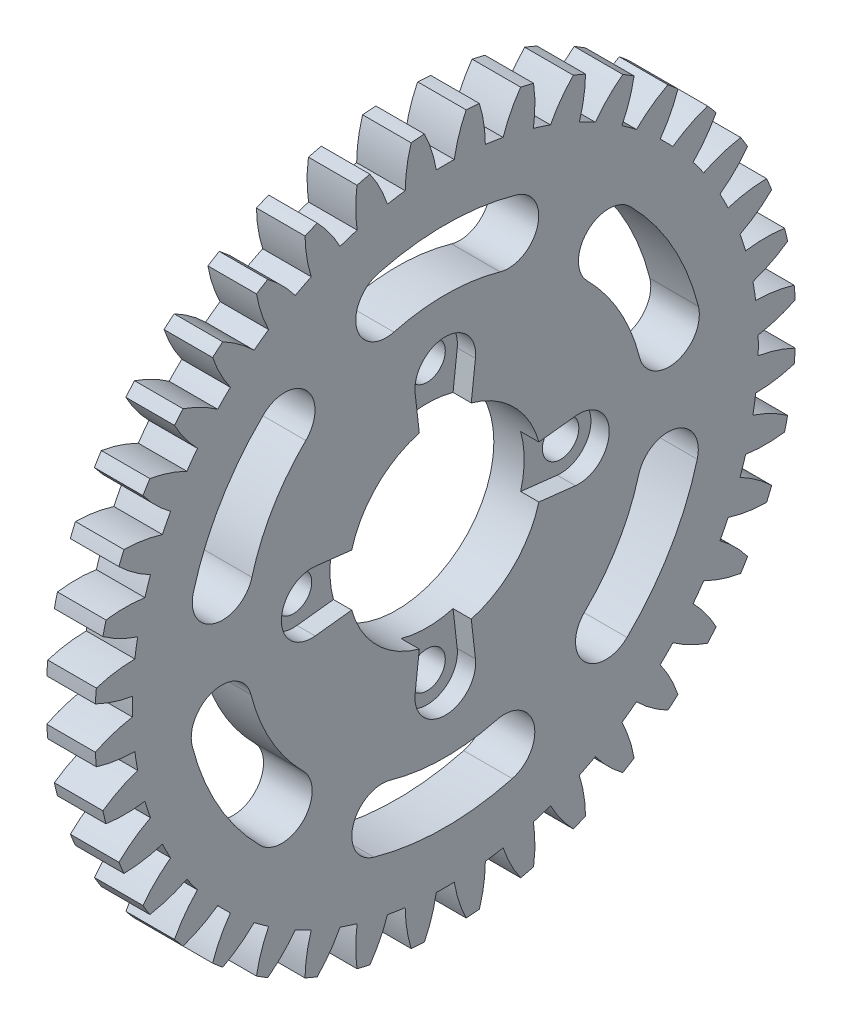
SolidWorks part; units mm, degrees
material "POM 乙缩醛共聚物"
ref_plane "Plane1" through (0, 0, 0) normal (0, 0, 1) x (1, 0, 0)
ref_plane "Plane2" through (0, 0, 0) normal (0, 1, 0) x (1, 0, 0)
ref_plane "Plane3" through (0, 0, 0) normal (1, 0, 0) x (0, 0, -1)
sketch "HoldingSke" plane through (0, 0, 0) normal (0, 1, 0) x (1, 0, 0)
  line L0 (0, 0) -> (0.5571, -0.4675)
  line L1 (-15, 0) -> (100, 0) construction
  line L2 (0, 0) -> (-2.1039, 2.3779)
  line L3 (0, 0) -> (-11.863, 4.5341)
  line L4 (0, 0) -> (6.6156, 5.5511)
  line L5 (0, 0) -> (-46.8476, -17.4728)
  line L6 (0, 0) -> (-3.3159, -2.2372)
  line L7 (-2.1039, 2.3779) -> (8.6586, 51.2059)
  line L8 (-76.2, 54.61) -> (-73.9, 54.61)
  line L9 (-67.7845, 28.3722) -> (-49.3413, 33.142)
  line L10 (-76.2, 71.12) -> (104.1128, 71.12)
  line L11 (0, 0) -> (-4, 0)
  line L12 (-76.2, 101.6) -> (-76.151, 101.6)
  line L13 (24.9733, 27.94) -> (52.9518, 28.4284)
  line L14 (24.9733, 27.94) -> (24.9743, 27.94)
  line L15 (24.9733, 27.94) -> (100.4006, 29.5858)
  line L16 (-63.627, -1.375) -> (-12.827, -1.375)
  circle A0 centre (0, 0) radius 8
  circle A1 centre (0, 0) radius 25.7803
  circle A2 centre (0, 0) radius 37.5
  circle A3 centre (0, 0) radius 8
  dimension "MHD" = 51.5605
  dimension "Hub_dia" = 75
  dimension "Bore" = 16
  dimension "MBD" = 16
  dimension "Num_teeth" = 40
  dimension "Pitch" = 0.7273
  dimension "Overall_len" = 50
  dimension "Show_teeth" = 40
  dimension "Thickness" = 4
  dimension "OAL" = 50.0001
  dimension "T_dim" = 2.3
  dimension "Ap" = 14.5
  dimension "H" = 19.05
  dimension "Pitch_radius" = 180.3128
  dimension "Width" = 4
  dimension "Backlash" = 0.049
  dimension "Addendum_fac" = 1
  dimension "Dedendum_fac" = 1.25
  dimension "Clearance_fac" = 0.25
  dimension "Dedendum_add" = 0.001
  dimension "Module" = 1.375
sketch "BasProSke" plane through (0, 0, 0) normal (0, 1, 0) x (1, 0, 0)
  line L0 (-10, 0) -> (60, 0) construction
  line L1 (0, 0) -> (0, 28.875)
  line L2 (0, 0) -> (4, 0)
  line L3 (4, 0) -> (4, 28.875)
  line L4 (4, 28.875) -> (0, 28.875)
  dimension "Thickness" = 4
  dimension "Diameter" = 57.75
revolve "Base-Revolve" add sketch "BasProSke" angle 360 about L0
sketch "TooCutSke" plane through (0, 0, 0) normal (1, 0, 0) x (0, 0, -1)
  line L1 (0, 0) -> (0, 107) construction
  line L2 (0, 0) -> (-1.1654, 27.4753) construction
  line L3 (0, 0) -> (-4.3124, 54.7946) construction
  line L4 (-1.1654, 27.4753) -> (-2.1562, 27.3973) construction
  arc A0 (0.7399, 25.7696) -> (-0.7399, 25.7696) centre (0, 0) ccw
  arc A1 (1.7331, 28.8484) -> (-1.7331, 28.8484) centre (0, 0) ccw
  circle A2 centre (0, 0) radius 27.5 construction
  circle A3 centre (0, 0) radius 26.6241 construction
  arc A4 (-0.7399, 25.7696) -> (-1.7331, 28.8484) centre (-11.5914, 23.9683) ccw
  arc A5 (1.7331, 28.8484) -> (0.7399, 25.7696) centre (11.5914, 23.9683) ccw
  dimension "Root_dia" = 51.5605
  dimension "Overcut_dia" = 57.8008
  dimension "Pitch_dia" = 55
  dimension "Base_dia" = 53.2481
  dimension "Flank_rad" = 11
  dimension "Half_ang" = 4.5
  dimension "Half_CT" = 0.9939
extrude "ToothCut" cut sketch "TooCutSke" along normal through all
fillet "Breaks" [suppressed] radius 0.0275
fillet "RootFillets" [suppressed] radius 0.3448
pattern_circular "TeethCuts" count 40 every 9 about axis through (-10, 0, 0) along (1, 0, 0) of "ToothCut", "RootFillets", "Breaks"
sketch "HubNeaOneSke" plane through (0, 0, 0) normal (-1, 0, 0) x (0, 0, 1)
  circle A0 centre (0, 0) radius 25.7803
  dimension "Diameter" = 51.5605
extrude "HubNearOne" [suppressed] add sketch "HubNeaOneSke" along normal blind 46.0001
sketch "HubNeaBotSke" plane through (0, 0, 0) normal (-1, 0, 0) x (0, 0, 1)
  circle A0 centre (0, 0) radius 25.7803
  dimension "Diameter" = 51.5605
extrude "HubNearBoth" [suppressed] add sketch "HubNeaBotSke" along normal blind 23
ref_plane "FarPln" through (4, 0, 0) normal (1, 0, 0) x (0, 0, -1)
sketch "HubFarSke" plane through (4, 0, 0) normal (1, 0, 0) x (0, 0, -1)
  circle A0 centre (0, 0) radius 25.7803
  dimension "Diameter" = 51.5605
extrude "HubFar" [suppressed] add sketch "HubFarSke" along normal blind 23
sketch "BorSke" plane through (0, 0, 0) normal (1, 0, 0) x (0, 0, -1)
  circle A0 centre (0, 0) radius 8
  dimension "Diameter" = 16
extrude "Bore" cut sketch "BorSke" along normal mid plane 100.0001
sketch "KeySke" plane through (0, 0, 0) normal (1, 0, 0) x (0, 0, -1)
  line L0 (-2.5, 0) -> (-2.5, 10.3)
  line L1 (-2.5, 10.3) -> (2.5, 10.3)
  line L2 (2.5, 10.3) -> (2.5, 0)
  line L3 (0, 0) -> (0, 34) construction
  line L4 (-2.5, 0) -> (2.5, 0)
  dimension "Offset" = 10.3
  dimension "Width" = 5
extrude "Keyway" [suppressed] cut sketch "KeySke" along normal mid plane 100.0001
pattern_circular "Keyway2" [suppressed] count 2 every 90 about axis through (-10, 0, 0) along (1, 0, 0)
sketch "草图1" plane through (4, 0, 0) normal (1, 0, 0) x (0, 0, -1)
  line L0 (10.7159, 2.4838) -> (7.7085, 2.1398)
  line L1 (10.7159, -2.4838) -> (7.7085, -2.1398)
  line L2 (-2.4838, -10.7159) -> (-2.1398, -7.7085)
  line L3 (2.4838, -10.7159) -> (2.1398, -7.7085)
  line L4 (-10.7159, 2.4838) -> (-7.7085, 2.1398)
  line L5 (-10.7159, -2.4838) -> (-7.7085, -2.1398)
  line L6 (2.4838, 10.7159) -> (2.1398, 7.7085)
  line L7 (-2.4838, 10.7159) -> (-2.1398, 7.7085)
  arc A0 (10.7159, -2.4838) -> (10.7159, 2.4838) centre (0, 0) ccw
  circle A1 centre (11, 0) radius 1.5
  arc A2 (10.7159, -2.4838) -> (10.7159, 2.4838) centre (11, 0) ccw
  circle A3 centre (0, 0) radius 8 construction
  arc A4 (-2.4838, -10.7159) -> (2.4838, -10.7159) centre (0, -11) ccw
  circle A5 centre (0, -11) radius 1.5
  arc A6 (-10.7159, 2.4838) -> (-10.7159, -2.4838) centre (-11, 0) ccw
  circle A7 centre (-11, 0) radius 1.5
  arc A8 (2.4838, 10.7159) -> (-2.4838, 10.7159) centre (0, 11) ccw
  circle A9 centre (0, 11) radius 1.5
  circle A10 centre (0, 0) radius 8
  point P31 (0, 0)
  dimension "D1" = 3
  dimension "D2" = 22
  dimension "D3" = 5
  dimension "D5" = 11
  dimension "D6" = 11
  dimension "D4" = 4
extrude "切除-拉伸2" cut sketch "草图1" against normal blind 1.5 contours A0 A2 A1 | A0 A1 | A0 A1 | A10 L1 A0 A1 L0 | A10 L2 A4 L3 A5 | A5 | A10 L4 A6 L5 A7 | A7 | A9 | A10 L6 A8 L7 A9
sketch "草图3" plane through (4, 0, 0) normal (1, 0, 0) x (0, 0, -1)
  line L0 (10.7159, 2.4838) -> (7.7085, 2.1398) construction
  line L1 (10.7159, -2.4838) -> (7.7085, -2.1398) construction
  line L2 (2.4838, -10.7159) -> (2.1398, -7.7085) construction
  line L3 (-2.4838, -10.7159) -> (-2.1398, -7.7085) construction
  line L4 (-10.7159, -2.4838) -> (-7.7085, -2.1398) construction
  line L5 (-10.7159, 2.4838) -> (-7.7085, 2.1398) construction
  line L6 (-2.4838, 10.7159) -> (-2.1398, 7.7085) construction
  line L7 (2.4838, 10.7159) -> (2.1398, 7.7085) construction
  line L8 (10.7159, 2.4838) -> (7.7085, 2.1398)
  line L9 (10.7159, -2.4838) -> (7.7085, -2.1398)
  line L10 (2.4838, -10.7159) -> (2.1398, -7.7085)
  line L11 (-2.4838, -10.7159) -> (-2.1398, -7.7085)
  line L12 (-10.7159, -2.4838) -> (-7.7085, -2.1398)
  line L13 (-10.7159, 2.4838) -> (-7.7085, 2.1398)
  line L14 (-2.4838, 10.7159) -> (-2.1398, 7.7085)
  line L15 (2.4838, 10.7159) -> (2.1398, 7.7085)
  line L16 (0, 0) -> (6.2134, 0) construction
  arc A0 (10.7159, -2.4838) -> (10.7159, 2.4838) centre (11, 0) ccw construction
  arc A1 (2.1398, -7.7085) -> (7.7085, -2.1398) centre (0, 0) ccw construction
  arc A2 (-2.4838, -10.7159) -> (2.4838, -10.7159) centre (0, -11) ccw construction
  arc A3 (-7.7085, -2.1398) -> (-2.1398, -7.7085) centre (0, 0) ccw construction
  arc A4 (-10.7159, 2.4838) -> (-10.7159, -2.4838) centre (-11, 0) ccw construction
  arc A5 (-2.1398, 7.7085) -> (-7.7085, 2.1398) centre (0, 0) ccw construction
  arc A6 (2.4838, 10.7159) -> (-2.4838, 10.7159) centre (0, 11) ccw construction
  arc A7 (7.7085, 2.1398) -> (2.1398, 7.7085) centre (0, 0) ccw construction
  arc A8 (10.7159, -2.4838) -> (10.7159, 2.4838) centre (11, 0) ccw
  arc A9 (2.1398, -7.7085) -> (7.7085, -2.1398) centre (0, 0) ccw
  arc A10 (-2.4838, -10.7159) -> (2.4838, -10.7159) centre (0, -11) ccw
  arc A11 (-7.7085, -2.1398) -> (-2.1398, -7.7085) centre (0, 0) ccw
  arc A12 (-10.7159, 2.4838) -> (-10.7159, -2.4838) centre (-11, 0) ccw
  arc A13 (-2.1398, 7.7085) -> (-7.7085, 2.1398) centre (0, 0) ccw
  arc A14 (2.4838, 10.7159) -> (-2.4838, 10.7159) centre (0, 11) ccw
  arc A15 (7.7085, 2.1398) -> (2.1398, 7.7085) centre (0, 0) ccw
  circle A16 centre (0, 11) radius 1.5
  circle A17 centre (0, -11) radius 1.5
  circle A18 centre (11, 0) radius 1.5
  circle A19 centre (-11, 0) radius 1.5
  arc A21 (13.4665, 13.4034) -> (18.4254, 4.6371) centre (0, 0) cw construction
  arc A22 (20.8499, 5.2473) -> (15.2385, 15.1671) centre (0, 0) ccw
  arc A23 (16.001, 4.027) -> (11.6946, 11.6398) centre (0, 0) ccw
  arc A24 (16.001, 4.027) -> (20.8499, 5.2473) centre (18.4254, 4.6371) ccw
  arc A25 (15.2385, 15.1671) -> (11.6946, 11.6398) centre (13.4665, 13.4034) ccw
  arc A26 (11.488, -11.8438) -> (15.9277, -4.3079) centre (0, 0) ccw
  arc A27 (11.488, -11.8438) -> (14.9692, -15.4329) centre (13.2286, -13.6384) ccw
  arc A28 (20.7543, -5.6134) -> (15.9277, -4.3079) centre (18.341, -4.9606) ccw
  arc A29 (14.9692, -15.4329) -> (20.7543, -5.6134) centre (0, 0) ccw
  arc A30 (18.341, -4.9606) -> (13.2286, -13.6384) centre (0, 0) cw construction
  arc A31 (-4.5131, -15.8708) -> (4.2331, -15.9478) centre (0, 0) ccw
  arc A32 (-4.5131, -15.8708) -> (-5.8807, -20.6801) centre (-5.1969, -18.2755) ccw
  arc A33 (5.5158, -20.7804) -> (4.2331, -15.9478) centre (4.8745, -18.3641) ccw
  arc A34 (-5.8807, -20.6801) -> (5.5158, -20.7804) centre (0, 0) ccw
  arc A35 (4.8745, -18.3641) -> (-5.1969, -18.2755) centre (0, 0) cw construction
  arc A36 (-16.001, -4.027) -> (-11.6946, -11.6398) centre (0, 0) ccw
  arc A37 (-16.001, -4.027) -> (-20.8499, -5.2473) centre (-18.4254, -4.6371) ccw
  arc A38 (-15.2385, -15.1671) -> (-11.6946, -11.6398) centre (-13.4665, -13.4034) ccw
  arc A39 (-20.8499, -5.2473) -> (-15.2385, -15.1671) centre (0, 0) ccw
  arc A40 (-13.4665, -13.4034) -> (-18.4254, -4.6371) centre (0, 0) cw construction
  arc A41 (-11.488, 11.8438) -> (-15.9277, 4.3079) centre (0, 0) ccw
  arc A42 (-11.488, 11.8438) -> (-14.9692, 15.4329) centre (-13.2286, 13.6384) ccw
  arc A43 (-20.7543, 5.6134) -> (-15.9277, 4.3079) centre (-18.341, 4.9606) ccw
  arc A44 (-14.9692, 15.4329) -> (-20.7543, 5.6134) centre (0, 0) ccw
  arc A45 (-18.341, 4.9606) -> (-13.2286, 13.6384) centre (0, 0) cw construction
  arc A46 (4.5131, 15.8708) -> (-4.2331, 15.9478) centre (0, 0) ccw
  arc A47 (4.5131, 15.8708) -> (5.8807, 20.6801) centre (5.1969, 18.2755) ccw
  arc A48 (-5.5158, 20.7804) -> (-4.2331, 15.9478) centre (-4.8745, 18.3641) ccw
  arc A49 (5.8807, 20.6801) -> (-5.5158, 20.7804) centre (0, 0) ccw
  arc A50 (-4.8745, 18.3641) -> (5.1969, 18.2755) centre (0, 0) cw construction
  arc A160 (-28.8237, 1.7209) -> (-25.7696, 0.7399) centre (-23.9683, 11.5914) ccw
  arc A161 (-25.7696, 0.7399) -> (-25.7696, -0.7399) centre (0, 0) ccw
  arc A162 (-25.7696, -0.7399) -> (-28.8237, -1.7209) centre (-23.9683, -11.5914) ccw
  arc A163 (-28.8237, -1.7209) -> (-28.738, -2.8093) centre (0, 0) ccw
  arc A164 (-28.738, -2.8093) -> (-25.5681, -3.3005) centre (-25.4865, 7.6992) ccw
  arc A165 (-25.5681, -3.3005) -> (-25.3366, -4.762) centre (0, 0) ccw
  arc A166 (-25.3366, -4.762) -> (-28.1996, -6.2088) centre (-21.8599, -15.1981) ccw
  arc A167 (-28.1996, -6.2088) -> (-27.9447, -7.2703) centre (0, 0) ccw
  arc A168 (-27.9447, -7.2703) -> (-24.737, -7.2596) centre (-26.3772, 3.6174) ccw
  arc A169 (-24.737, -7.2596) -> (-24.2797, -8.6669) centre (0, 0) ccw
  arc A170 (-24.2797, -8.6669) -> (-26.8811, -10.5437) centre (-19.2133, -18.4307) ccw
  arc A171 (-26.8811, -10.5437) -> (-26.4634, -11.5523) centre (0, 0) ccw
  arc A172 (-26.4634, -11.5523) -> (-23.2968, -11.0399) centre (-26.6183, -0.5534) ccw
  arc A173 (-23.2968, -11.0399) -> (-22.625, -12.3584) centre (0, 0) ccw
  arc A174 (-22.625, -12.3584) -> (-24.9008, -14.619) centre (-16.0936, -21.2094) ccw
  arc A175 (-24.9008, -14.619) -> (-24.3304, -15.5499) centre (0, 0) ccw
  arc A176 (-24.3304, -15.5499) -> (-21.2829, -14.5485) centre (-26.204, -4.7106) ccw
  arc A177 (-21.2829, -14.5485) -> (-20.4132, -15.7456) centre (0, 0) ccw
  arc A178 (-20.4132, -15.7456) -> (-22.3073, -18.3344) centre (-12.5775, -23.4658) ccw
  arc A179 (-22.3073, -18.3344) -> (-21.5983, -19.1645) centre (0, 0) ccw
  arc A180 (-21.5983, -19.1645) -> (-18.745, -17.6987) centre (-25.1445, -8.7518) ccw
  arc A181 (-18.745, -17.6987) -> (-17.6987, -18.745) centre (0, 0) ccw
  arc A182 (-17.6987, -18.745) -> (-19.1645, -21.5983) centre (-8.7518, -25.1445) ccw
  arc A183 (-19.1645, -21.5983) -> (-18.3344, -22.3073) centre (0, 0) ccw
  arc A184 (-18.3344, -22.3073) -> (-15.7456, -20.4132) centre (-23.4658, -12.5775) ccw
  arc A185 (-15.7456, -20.4132) -> (-14.5485, -21.2829) centre (0, 0) ccw
  arc A186 (-14.5485, -21.2829) -> (-15.5499, -24.3304) centre (-4.7106, -26.204) ccw
  arc A187 (-15.5499, -24.3304) -> (-14.619, -24.9008) centre (0, 0) ccw
  arc A188 (-14.619, -24.9008) -> (-12.3584, -22.625) centre (-21.2094, -16.0936) ccw
  arc A189 (-12.3584, -22.625) -> (-11.0399, -23.2968) centre (0, 0) ccw
  arc A190 (-11.0399, -23.2968) -> (-11.5523, -26.4634) centre (-0.5534, -26.6183) ccw
  arc A191 (-11.5523, -26.4634) -> (-10.5437, -26.8811) centre (0, 0) ccw
  arc A192 (-10.5437, -26.8811) -> (-8.6669, -24.2797) centre (-18.4307, -19.2133) ccw
  arc A193 (-8.6669, -24.2797) -> (-7.2596, -24.737) centre (0, 0) ccw
  arc A194 (-7.2596, -24.737) -> (-7.2703, -27.9447) centre (3.6174, -26.3772) ccw
  arc A195 (-7.2703, -27.9447) -> (-6.2088, -28.1996) centre (0, 0) ccw
  arc A196 (-6.2088, -28.1996) -> (-4.762, -25.3366) centre (-15.1981, -21.8599) ccw
  arc A197 (-4.762, -25.3366) -> (-3.3005, -25.5681) centre (0, 0) ccw
  arc A198 (-3.3005, -25.5681) -> (-2.8093, -28.738) centre (7.6992, -25.4865) ccw
  arc A199 (-2.8093, -28.738) -> (-1.7209, -28.8237) centre (0, 0) ccw
  arc A200 (-1.7209, -28.8237) -> (-0.7399, -25.7696) centre (-11.5914, -23.9683) ccw
  arc A201 (-0.7399, -25.7696) -> (0.7399, -25.7696) centre (0, 0) ccw
  arc A202 (0.7399, -25.7696) -> (1.7209, -28.8237) centre (11.5914, -23.9683) ccw
  arc A203 (1.7209, -28.8237) -> (2.8093, -28.738) centre (0, 0) ccw
  arc A204 (2.8093, -28.738) -> (3.3005, -25.5681) centre (-7.6992, -25.4865) ccw
  arc A205 (3.3005, -25.5681) -> (4.762, -25.3366) centre (0, 0) ccw
  arc A206 (4.762, -25.3366) -> (6.2088, -28.1996) centre (15.1981, -21.8599) ccw
  arc A207 (6.2088, -28.1996) -> (7.2703, -27.9447) centre (0, 0) ccw
  arc A208 (7.2703, -27.9447) -> (7.2596, -24.737) centre (-3.6174, -26.3772) ccw
  arc A209 (7.2596, -24.737) -> (8.6669, -24.2797) centre (0, 0) ccw
  arc A210 (8.6669, -24.2797) -> (10.5437, -26.8811) centre (18.4307, -19.2133) ccw
  arc A211 (10.5437, -26.8811) -> (11.5523, -26.4634) centre (0, 0) ccw
  arc A212 (11.5523, -26.4634) -> (11.0399, -23.2968) centre (0.5534, -26.6183) ccw
  arc A213 (11.0399, -23.2968) -> (12.3584, -22.625) centre (0, 0) ccw
  arc A214 (12.3584, -22.625) -> (14.619, -24.9008) centre (21.2094, -16.0936) ccw
  arc A215 (14.619, -24.9008) -> (15.5499, -24.3304) centre (0, 0) ccw
  arc A216 (15.5499, -24.3304) -> (14.5485, -21.2829) centre (4.7106, -26.204) ccw
  arc A217 (14.5485, -21.2829) -> (15.7456, -20.4132) centre (0, 0) ccw
  arc A218 (15.7456, -20.4132) -> (18.3344, -22.3073) centre (23.4658, -12.5775) ccw
  arc A219 (18.3344, -22.3073) -> (19.1645, -21.5983) centre (0, 0) ccw
  arc A220 (19.1645, -21.5983) -> (17.6987, -18.745) centre (8.7518, -25.1445) ccw
  arc A221 (17.6987, -18.745) -> (18.745, -17.6987) centre (0, 0) ccw
  arc A222 (18.745, -17.6987) -> (21.5983, -19.1645) centre (25.1445, -8.7518) ccw
  arc A223 (21.5983, -19.1645) -> (22.3073, -18.3344) centre (0, 0) ccw
  arc A224 (22.3073, -18.3344) -> (20.4132, -15.7456) centre (12.5775, -23.4658) ccw
  arc A225 (20.4132, -15.7456) -> (21.2829, -14.5485) centre (0, 0) ccw
  arc A226 (21.2829, -14.5485) -> (24.3304, -15.5499) centre (26.204, -4.7106) ccw
  arc A227 (24.3304, -15.5499) -> (24.9008, -14.619) centre (0, 0) ccw
  arc A228 (24.9008, -14.619) -> (22.625, -12.3584) centre (16.0936, -21.2094) ccw
  arc A229 (22.625, -12.3584) -> (23.2968, -11.0399) centre (0, 0) ccw
  arc A230 (23.2968, -11.0399) -> (26.4634, -11.5523) centre (26.6183, -0.5534) ccw
  arc A231 (26.4634, -11.5523) -> (26.8811, -10.5437) centre (0, 0) ccw
  arc A232 (26.8811, -10.5437) -> (24.2797, -8.6669) centre (19.2133, -18.4307) ccw
  arc A233 (24.2797, -8.6669) -> (24.737, -7.2596) centre (0, 0) ccw
  arc A234 (24.737, -7.2596) -> (27.9447, -7.2703) centre (26.3772, 3.6174) ccw
  arc A235 (27.9447, -7.2703) -> (28.1996, -6.2088) centre (0, 0) ccw
  arc A236 (28.1996, -6.2088) -> (25.3366, -4.762) centre (21.8599, -15.1981) ccw
  arc A237 (25.3366, -4.762) -> (25.5681, -3.3005) centre (0, 0) ccw
  arc A238 (25.5681, -3.3005) -> (28.738, -2.8093) centre (25.4865, 7.6992) ccw
  arc A239 (28.738, -2.8093) -> (28.8237, -1.7209) centre (0, 0) ccw
  arc A240 (28.8237, -1.7209) -> (25.7696, -0.7399) centre (23.9683, -11.5914) ccw
  arc A241 (25.7696, -0.7399) -> (25.7696, 0.7399) centre (0, 0) ccw
  arc A242 (25.7696, 0.7399) -> (28.8237, 1.7209) centre (23.9683, 11.5914) ccw
  arc A243 (28.8237, 1.7209) -> (28.738, 2.8093) centre (0, 0) ccw
  arc A244 (28.738, 2.8093) -> (25.5681, 3.3005) centre (25.4865, -7.6992) ccw
  arc A245 (25.5681, 3.3005) -> (25.3366, 4.762) centre (0, 0) ccw
  arc A246 (25.3366, 4.762) -> (28.1996, 6.2088) centre (21.8599, 15.1981) ccw
  arc A247 (28.1996, 6.2088) -> (27.9447, 7.2703) centre (0, 0) ccw
  arc A248 (27.9447, 7.2703) -> (24.737, 7.2596) centre (26.3772, -3.6174) ccw
  arc A249 (24.737, 7.2596) -> (24.2797, 8.6669) centre (0, 0) ccw
  arc A250 (24.2797, 8.6669) -> (26.8811, 10.5437) centre (19.2133, 18.4307) ccw
  arc A251 (26.8811, 10.5437) -> (26.4634, 11.5523) centre (0, 0) ccw
  arc A252 (26.4634, 11.5523) -> (23.2968, 11.0399) centre (26.6183, 0.5534) ccw
  arc A253 (23.2968, 11.0399) -> (22.625, 12.3584) centre (0, 0) ccw
  arc A254 (22.625, 12.3584) -> (24.9008, 14.619) centre (16.0936, 21.2094) ccw
  arc A255 (24.9008, 14.619) -> (24.3304, 15.5499) centre (0, 0) ccw
  arc A256 (24.3304, 15.5499) -> (21.2829, 14.5485) centre (26.204, 4.7106) ccw
  arc A257 (21.2829, 14.5485) -> (20.4132, 15.7456) centre (0, 0) ccw
  arc A258 (20.4132, 15.7456) -> (22.3073, 18.3344) centre (12.5775, 23.4658) ccw
  arc A259 (22.3073, 18.3344) -> (21.5983, 19.1645) centre (0, 0) ccw
  arc A260 (21.5983, 19.1645) -> (18.745, 17.6987) centre (25.1445, 8.7518) ccw
  arc A261 (18.745, 17.6987) -> (17.6987, 18.745) centre (0, 0) ccw
  arc A262 (17.6987, 18.745) -> (19.1645, 21.5983) centre (8.7518, 25.1445) ccw
  arc A263 (19.1645, 21.5983) -> (18.3344, 22.3073) centre (0, 0) ccw
  arc A264 (18.3344, 22.3073) -> (15.7456, 20.4132) centre (23.4658, 12.5775) ccw
  arc A265 (15.7456, 20.4132) -> (14.5485, 21.2829) centre (0, 0) ccw
  arc A266 (14.5485, 21.2829) -> (15.5499, 24.3304) centre (4.7106, 26.204) ccw
  arc A267 (15.5499, 24.3304) -> (14.619, 24.9008) centre (0, 0) ccw
  arc A268 (14.619, 24.9008) -> (12.3584, 22.625) centre (21.2094, 16.0936) ccw
  arc A269 (12.3584, 22.625) -> (11.0399, 23.2968) centre (0, 0) ccw
  arc A270 (11.0399, 23.2968) -> (11.5523, 26.4634) centre (0.5534, 26.6183) ccw
  arc A271 (11.5523, 26.4634) -> (10.5437, 26.8811) centre (0, 0) ccw
  arc A272 (10.5437, 26.8811) -> (8.6669, 24.2797) centre (18.4307, 19.2133) ccw
  arc A273 (8.6669, 24.2797) -> (7.2596, 24.737) centre (0, 0) ccw
  arc A274 (7.2596, 24.737) -> (7.2703, 27.9447) centre (-3.6174, 26.3772) ccw
  arc A275 (7.2703, 27.9447) -> (6.2088, 28.1996) centre (0, 0) ccw
  arc A276 (6.2088, 28.1996) -> (4.762, 25.3366) centre (15.1981, 21.8599) ccw
  arc A277 (4.762, 25.3366) -> (3.3005, 25.5681) centre (0, 0) ccw
  arc A278 (3.3005, 25.5681) -> (2.8093, 28.738) centre (-7.6992, 25.4865) ccw
  arc A279 (2.8093, 28.738) -> (1.7209, 28.8237) centre (0, 0) ccw
  arc A280 (1.7209, 28.8237) -> (0.7399, 25.7696) centre (11.5914, 23.9683) ccw
  arc A281 (0.7399, 25.7696) -> (-0.7399, 25.7696) centre (0, 0) ccw
  arc A282 (-0.7399, 25.7696) -> (-1.7209, 28.8237) centre (-11.5914, 23.9683) ccw
  arc A283 (-1.7209, 28.8237) -> (-2.8093, 28.738) centre (0, 0) ccw
  arc A284 (-2.8093, 28.738) -> (-3.3005, 25.5681) centre (7.6992, 25.4865) ccw
  arc A285 (-3.3005, 25.5681) -> (-4.762, 25.3366) centre (0, 0) ccw
  arc A286 (-4.762, 25.3366) -> (-6.2088, 28.1996) centre (-15.1981, 21.8599) ccw
  arc A287 (-6.2088, 28.1996) -> (-7.2703, 27.9447) centre (0, 0) ccw
  arc A288 (-7.2703, 27.9447) -> (-7.2596, 24.737) centre (3.6174, 26.3772) ccw
  arc A289 (-7.2596, 24.737) -> (-8.6669, 24.2797) centre (0, 0) ccw
  arc A290 (-8.6669, 24.2797) -> (-10.5437, 26.8811) centre (-18.4307, 19.2133) ccw
  arc A291 (-10.5437, 26.8811) -> (-11.5523, 26.4634) centre (0, 0) ccw
  arc A292 (-11.5523, 26.4634) -> (-11.0399, 23.2968) centre (-0.5534, 26.6183) ccw
  arc A293 (-11.0399, 23.2968) -> (-12.3584, 22.625) centre (0, 0) ccw
  arc A294 (-12.3584, 22.625) -> (-14.619, 24.9008) centre (-21.2094, 16.0936) ccw
  arc A295 (-14.619, 24.9008) -> (-15.5499, 24.3304) centre (0, 0) ccw
  arc A296 (-15.5499, 24.3304) -> (-14.5485, 21.2829) centre (-4.7106, 26.204) ccw
  arc A297 (-14.5485, 21.2829) -> (-15.7456, 20.4132) centre (0, 0) ccw
  arc A298 (-15.7456, 20.4132) -> (-18.3344, 22.3073) centre (-23.4658, 12.5775) ccw
  arc A299 (-18.3344, 22.3073) -> (-19.1645, 21.5983) centre (0, 0) ccw
  arc A300 (-19.1645, 21.5983) -> (-17.6987, 18.745) centre (-8.7518, 25.1445) ccw
  arc A301 (-17.6987, 18.745) -> (-18.745, 17.6987) centre (0, 0) ccw
  arc A302 (-18.745, 17.6987) -> (-21.5983, 19.1645) centre (-25.1445, 8.7518) ccw
  arc A303 (-21.5983, 19.1645) -> (-22.3073, 18.3344) centre (0, 0) ccw
  arc A304 (-22.3073, 18.3344) -> (-20.4132, 15.7456) centre (-12.5775, 23.4658) ccw
  arc A305 (-20.4132, 15.7456) -> (-21.2829, 14.5485) centre (0, 0) ccw
  arc A306 (-21.2829, 14.5485) -> (-24.3304, 15.5499) centre (-26.204, 4.7106) ccw
  arc A307 (-24.3304, 15.5499) -> (-24.9008, 14.619) centre (0, 0) ccw
  arc A308 (-24.9008, 14.619) -> (-22.625, 12.3584) centre (-16.0936, 21.2094) ccw
  arc A309 (-22.625, 12.3584) -> (-23.2968, 11.0399) centre (0, 0) ccw
  arc A310 (-23.2968, 11.0399) -> (-26.4634, 11.5523) centre (-26.6183, 0.5534) ccw
  arc A311 (-26.4634, 11.5523) -> (-26.8811, 10.5437) centre (0, 0) ccw
  arc A312 (-26.8811, 10.5437) -> (-24.2797, 8.6669) centre (-19.2133, 18.4307) ccw
  arc A313 (-24.2797, 8.6669) -> (-24.737, 7.2596) centre (0, 0) ccw
  arc A314 (-24.737, 7.2596) -> (-27.9447, 7.2703) centre (-26.3772, -3.6174) ccw
  arc A315 (-27.9447, 7.2703) -> (-28.1996, 6.2088) centre (0, 0) ccw
  arc A316 (-28.1996, 6.2088) -> (-25.3366, 4.762) centre (-21.8599, 15.1981) ccw
  arc A317 (-25.3366, 4.762) -> (-25.5681, 3.3005) centre (0, 0) ccw
  arc A318 (-25.5681, 3.3005) -> (-28.738, 2.8093) centre (-25.4865, -7.6992) ccw
  arc A319 (-28.738, 2.8093) -> (-28.8237, 1.7209) centre (0, 0) ccw
  arc A320 (-28.8237, 1.7209) -> (-25.7696, 0.7399) centre (-23.9683, 11.5914) ccw
  arc A321 (-25.7696, 0.7399) -> (-25.7696, -0.7399) centre (0, 0) ccw
  arc A322 (-25.7696, -0.7399) -> (-28.8237, -1.7209) centre (-23.9683, -11.5914) ccw
  arc A323 (-28.8237, -1.7209) -> (-28.738, -2.8093) centre (0, 0) ccw
  arc A324 (-28.738, -2.8093) -> (-25.5681, -3.3005) centre (-25.4865, 7.6992) ccw
  arc A325 (-25.5681, -3.3005) -> (-25.3366, -4.762) centre (0, 0) ccw
  arc A326 (-25.3366, -4.762) -> (-28.1996, -6.2088) centre (-21.8599, -15.1981) ccw
  arc A327 (-28.1996, -6.2088) -> (-27.9447, -7.2703) centre (0, 0) ccw
  arc A328 (-27.9447, -7.2703) -> (-24.737, -7.2596) centre (-26.3772, 3.6174) ccw
  arc A329 (-24.737, -7.2596) -> (-24.2797, -8.6669) centre (0, 0) ccw
  arc A330 (-24.2797, -8.6669) -> (-26.8811, -10.5437) centre (-19.2133, -18.4307) ccw
  arc A331 (-26.8811, -10.5437) -> (-26.4634, -11.5523) centre (0, 0) ccw
  arc A332 (-26.4634, -11.5523) -> (-23.2968, -11.0399) centre (-26.6183, -0.5534) ccw
  arc A333 (-23.2968, -11.0399) -> (-22.625, -12.3584) centre (0, 0) ccw
  arc A334 (-22.625, -12.3584) -> (-24.9008, -14.619) centre (-16.0936, -21.2094) ccw
  arc A335 (-24.9008, -14.619) -> (-24.3304, -15.5499) centre (0, 0) ccw
  arc A336 (-24.3304, -15.5499) -> (-21.2829, -14.5485) centre (-26.204, -4.7106) ccw
  arc A337 (-21.2829, -14.5485) -> (-20.4132, -15.7456) centre (0, 0) ccw
  arc A338 (-20.4132, -15.7456) -> (-22.3073, -18.3344) centre (-12.5775, -23.4658) ccw
  arc A339 (-22.3073, -18.3344) -> (-21.5983, -19.1645) centre (0, 0) ccw
  arc A340 (-21.5983, -19.1645) -> (-18.745, -17.6987) centre (-25.1445, -8.7518) ccw
  arc A341 (-18.745, -17.6987) -> (-17.6987, -18.745) centre (0, 0) ccw
  arc A342 (-17.6987, -18.745) -> (-19.1645, -21.5983) centre (-8.7518, -25.1445) ccw
  arc A343 (-19.1645, -21.5983) -> (-18.3344, -22.3073) centre (0, 0) ccw
  arc A344 (-18.3344, -22.3073) -> (-15.7456, -20.4132) centre (-23.4658, -12.5775) ccw
  arc A345 (-15.7456, -20.4132) -> (-14.5485, -21.2829) centre (0, 0) ccw
  arc A346 (-14.5485, -21.2829) -> (-15.5499, -24.3304) centre (-4.7106, -26.204) ccw
  arc A347 (-15.5499, -24.3304) -> (-14.619, -24.9008) centre (0, 0) ccw
  arc A348 (-14.619, -24.9008) -> (-12.3584, -22.625) centre (-21.2094, -16.0936) ccw
  arc A349 (-12.3584, -22.625) -> (-11.0399, -23.2968) centre (0, 0) ccw
  arc A350 (-11.0399, -23.2968) -> (-11.5523, -26.4634) centre (-0.5534, -26.6183) ccw
  arc A351 (-11.5523, -26.4634) -> (-10.5437, -26.8811) centre (0, 0) ccw
  arc A352 (-10.5437, -26.8811) -> (-8.6669, -24.2797) centre (-18.4307, -19.2133) ccw
  arc A353 (-8.6669, -24.2797) -> (-7.2596, -24.737) centre (0, 0) ccw
  arc A354 (-7.2596, -24.737) -> (-7.2703, -27.9447) centre (3.6174, -26.3772) ccw
  arc A355 (-7.2703, -27.9447) -> (-6.2088, -28.1996) centre (0, 0) ccw
  arc A356 (-6.2088, -28.1996) -> (-4.762, -25.3366) centre (-15.1981, -21.8599) ccw
  arc A357 (-4.762, -25.3366) -> (-3.3005, -25.5681) centre (0, 0) ccw
  arc A358 (-3.3005, -25.5681) -> (-2.8093, -28.738) centre (7.6992, -25.4865) ccw
  arc A359 (-2.8093, -28.738) -> (-1.7209, -28.8237) centre (0, 0) ccw
  arc A360 (-1.7209, -28.8237) -> (-0.7399, -25.7696) centre (-11.5914, -23.9683) ccw
  arc A361 (-0.7399, -25.7696) -> (0.7399, -25.7696) centre (0, 0) ccw
  arc A362 (0.7399, -25.7696) -> (1.7209, -28.8237) centre (11.5914, -23.9683) ccw
  arc A363 (1.7209, -28.8237) -> (2.8093, -28.738) centre (0, 0) ccw
  arc A364 (2.8093, -28.738) -> (3.3005, -25.5681) centre (-7.6992, -25.4865) ccw
  arc A365 (3.3005, -25.5681) -> (4.762, -25.3366) centre (0, 0) ccw
  arc A366 (4.762, -25.3366) -> (6.2088, -28.1996) centre (15.1981, -21.8599) ccw
  arc A367 (6.2088, -28.1996) -> (7.2703, -27.9447) centre (0, 0) ccw
  arc A368 (7.2703, -27.9447) -> (7.2596, -24.737) centre (-3.6174, -26.3772) ccw
  arc A369 (7.2596, -24.737) -> (8.6669, -24.2797) centre (0, 0) ccw
  arc A370 (8.6669, -24.2797) -> (10.5437, -26.8811) centre (18.4307, -19.2133) ccw
  arc A371 (10.5437, -26.8811) -> (11.5523, -26.4634) centre (0, 0) ccw
  arc A372 (11.5523, -26.4634) -> (11.0399, -23.2968) centre (0.5534, -26.6183) ccw
  arc A373 (11.0399, -23.2968) -> (12.3584, -22.625) centre (0, 0) ccw
  arc A374 (12.3584, -22.625) -> (14.619, -24.9008) centre (21.2094, -16.0936) ccw
  arc A375 (14.619, -24.9008) -> (15.5499, -24.3304) centre (0, 0) ccw
  arc A376 (15.5499, -24.3304) -> (14.5485, -21.2829) centre (4.7106, -26.204) ccw
  arc A377 (14.5485, -21.2829) -> (15.7456, -20.4132) centre (0, 0) ccw
  arc A378 (15.7456, -20.4132) -> (18.3344, -22.3073) centre (23.4658, -12.5775) ccw
  arc A379 (18.3344, -22.3073) -> (19.1645, -21.5983) centre (0, 0) ccw
  arc A380 (19.1645, -21.5983) -> (17.6987, -18.745) centre (8.7518, -25.1445) ccw
  arc A381 (17.6987, -18.745) -> (18.745, -17.6987) centre (0, 0) ccw
  arc A382 (18.745, -17.6987) -> (21.5983, -19.1645) centre (25.1445, -8.7518) ccw
  arc A383 (21.5983, -19.1645) -> (22.3073, -18.3344) centre (0, 0) ccw
  arc A384 (22.3073, -18.3344) -> (20.4132, -15.7456) centre (12.5775, -23.4658) ccw
  arc A385 (20.4132, -15.7456) -> (21.2829, -14.5485) centre (0, 0) ccw
  arc A386 (21.2829, -14.5485) -> (24.3304, -15.5499) centre (26.204, -4.7106) ccw
  arc A387 (24.3304, -15.5499) -> (24.9008, -14.619) centre (0, 0) ccw
  arc A388 (24.9008, -14.619) -> (22.625, -12.3584) centre (16.0936, -21.2094) ccw
  arc A389 (22.625, -12.3584) -> (23.2968, -11.0399) centre (0, 0) ccw
  arc A390 (23.2968, -11.0399) -> (26.4634, -11.5523) centre (26.6183, -0.5534) ccw
  arc A391 (26.4634, -11.5523) -> (26.8811, -10.5437) centre (0, 0) ccw
  arc A392 (26.8811, -10.5437) -> (24.2797, -8.6669) centre (19.2133, -18.4307) ccw
  arc A393 (24.2797, -8.6669) -> (24.737, -7.2596) centre (0, 0) ccw
  arc A394 (24.737, -7.2596) -> (27.9447, -7.2703) centre (26.3772, 3.6174) ccw
  arc A395 (27.9447, -7.2703) -> (28.1996, -6.2088) centre (0, 0) ccw
  arc A396 (28.1996, -6.2088) -> (25.3366, -4.762) centre (21.8599, -15.1981) ccw
  arc A397 (25.3366, -4.762) -> (25.5681, -3.3005) centre (0, 0) ccw
  arc A398 (25.5681, -3.3005) -> (28.738, -2.8093) centre (25.4865, 7.6992) ccw
  arc A399 (28.738, -2.8093) -> (28.8237, -1.7209) centre (0, 0) ccw
  arc A400 (28.8237, -1.7209) -> (25.7696, -0.7399) centre (23.9683, -11.5914) ccw
  arc A401 (25.7696, -0.7399) -> (25.7696, 0.7399) centre (0, 0) ccw
  arc A402 (25.7696, 0.7399) -> (28.8237, 1.7209) centre (23.9683, 11.5914) ccw
  arc A403 (28.8237, 1.7209) -> (28.738, 2.8093) centre (0, 0) ccw
  arc A404 (28.738, 2.8093) -> (25.5681, 3.3005) centre (25.4865, -7.6992) ccw
  arc A405 (25.5681, 3.3005) -> (25.3366, 4.762) centre (0, 0) ccw
  arc A406 (25.3366, 4.762) -> (28.1996, 6.2088) centre (21.8599, 15.1981) ccw
  arc A407 (28.1996, 6.2088) -> (27.9447, 7.2703) centre (0, 0) ccw
  arc A408 (27.9447, 7.2703) -> (24.737, 7.2596) centre (26.3772, -3.6174) ccw
  arc A409 (24.737, 7.2596) -> (24.2797, 8.6669) centre (0, 0) ccw
  arc A410 (24.2797, 8.6669) -> (26.8811, 10.5437) centre (19.2133, 18.4307) ccw
  arc A411 (26.8811, 10.5437) -> (26.4634, 11.5523) centre (0, 0) ccw
  arc A412 (26.4634, 11.5523) -> (23.2968, 11.0399) centre (26.6183, 0.5534) ccw
  arc A413 (23.2968, 11.0399) -> (22.625, 12.3584) centre (0, 0) ccw
  arc A414 (22.625, 12.3584) -> (24.9008, 14.619) centre (16.0936, 21.2094) ccw
  arc A415 (24.9008, 14.619) -> (24.3304, 15.5499) centre (0, 0) ccw
  arc A416 (24.3304, 15.5499) -> (21.2829, 14.5485) centre (26.204, 4.7106) ccw
  arc A417 (21.2829, 14.5485) -> (20.4132, 15.7456) centre (0, 0) ccw
  arc A418 (20.4132, 15.7456) -> (22.3073, 18.3344) centre (12.5775, 23.4658) ccw
  arc A419 (22.3073, 18.3344) -> (21.5983, 19.1645) centre (0, 0) ccw
  arc A420 (21.5983, 19.1645) -> (18.745, 17.6987) centre (25.1445, 8.7518) ccw
  arc A421 (18.745, 17.6987) -> (17.6987, 18.745) centre (0, 0) ccw
  arc A422 (17.6987, 18.745) -> (19.1645, 21.5983) centre (8.7518, 25.1445) ccw
  arc A423 (19.1645, 21.5983) -> (18.3344, 22.3073) centre (0, 0) ccw
  arc A424 (18.3344, 22.3073) -> (15.7456, 20.4132) centre (23.4658, 12.5775) ccw
  arc A425 (15.7456, 20.4132) -> (14.5485, 21.2829) centre (0, 0) ccw
  arc A426 (14.5485, 21.2829) -> (15.5499, 24.3304) centre (4.7106, 26.204) ccw
  arc A427 (15.5499, 24.3304) -> (14.619, 24.9008) centre (0, 0) ccw
  arc A428 (14.619, 24.9008) -> (12.3584, 22.625) centre (21.2094, 16.0936) ccw
  arc A429 (12.3584, 22.625) -> (11.0399, 23.2968) centre (0, 0) ccw
  arc A430 (11.0399, 23.2968) -> (11.5523, 26.4634) centre (0.5534, 26.6183) ccw
  arc A431 (11.5523, 26.4634) -> (10.5437, 26.8811) centre (0, 0) ccw
  arc A432 (10.5437, 26.8811) -> (8.6669, 24.2797) centre (18.4307, 19.2133) ccw
  arc A433 (8.6669, 24.2797) -> (7.2596, 24.737) centre (0, 0) ccw
  arc A434 (7.2596, 24.737) -> (7.2703, 27.9447) centre (-3.6174, 26.3772) ccw
  arc A435 (7.2703, 27.9447) -> (6.2088, 28.1996) centre (0, 0) ccw
  arc A436 (6.2088, 28.1996) -> (4.762, 25.3366) centre (15.1981, 21.8599) ccw
  arc A437 (4.762, 25.3366) -> (3.3005, 25.5681) centre (0, 0) ccw
  arc A438 (3.3005, 25.5681) -> (2.8093, 28.738) centre (-7.6992, 25.4865) ccw
  arc A439 (2.8093, 28.738) -> (1.7209, 28.8237) centre (0, 0) ccw
  arc A440 (1.7209, 28.8237) -> (0.7399, 25.7696) centre (11.5914, 23.9683) ccw
  arc A441 (0.7399, 25.7696) -> (-0.7399, 25.7696) centre (0, 0) ccw
  arc A442 (-0.7399, 25.7696) -> (-1.7209, 28.8237) centre (-11.5914, 23.9683) ccw
  arc A443 (-1.7209, 28.8237) -> (-2.8093, 28.738) centre (0, 0) ccw
  arc A444 (-2.8093, 28.738) -> (-3.3005, 25.5681) centre (7.6992, 25.4865) ccw
  arc A445 (-3.3005, 25.5681) -> (-4.762, 25.3366) centre (0, 0) ccw
  arc A446 (-4.762, 25.3366) -> (-6.2088, 28.1996) centre (-15.1981, 21.8599) ccw
  arc A447 (-6.2088, 28.1996) -> (-7.2703, 27.9447) centre (0, 0) ccw
  arc A448 (-7.2703, 27.9447) -> (-7.2596, 24.737) centre (3.6174, 26.3772) ccw
  arc A449 (-7.2596, 24.737) -> (-8.6669, 24.2797) centre (0, 0) ccw
  arc A450 (-8.6669, 24.2797) -> (-10.5437, 26.8811) centre (-18.4307, 19.2133) ccw
  arc A451 (-10.5437, 26.8811) -> (-11.5523, 26.4634) centre (0, 0) ccw
  arc A452 (-11.5523, 26.4634) -> (-11.0399, 23.2968) centre (-0.5534, 26.6183) ccw
  arc A453 (-11.0399, 23.2968) -> (-12.3584, 22.625) centre (0, 0) ccw
  arc A454 (-12.3584, 22.625) -> (-14.619, 24.9008) centre (-21.2094, 16.0936) ccw
  arc A455 (-14.619, 24.9008) -> (-15.5499, 24.3304) centre (0, 0) ccw
  arc A456 (-15.5499, 24.3304) -> (-14.5485, 21.2829) centre (-4.7106, 26.204) ccw
  arc A457 (-14.5485, 21.2829) -> (-15.7456, 20.4132) centre (0, 0) ccw
  arc A458 (-15.7456, 20.4132) -> (-18.3344, 22.3073) centre (-23.4658, 12.5775) ccw
  arc A459 (-18.3344, 22.3073) -> (-19.1645, 21.5983) centre (0, 0) ccw
  arc A460 (-19.1645, 21.5983) -> (-17.6987, 18.745) centre (-8.7518, 25.1445) ccw
  arc A461 (-17.6987, 18.745) -> (-18.745, 17.6987) centre (0, 0) ccw
  arc A462 (-18.745, 17.6987) -> (-21.5983, 19.1645) centre (-25.1445, 8.7518) ccw
  arc A463 (-21.5983, 19.1645) -> (-22.3073, 18.3344) centre (0, 0) ccw
  arc A464 (-22.3073, 18.3344) -> (-20.4132, 15.7456) centre (-12.5775, 23.4658) ccw
  arc A465 (-20.4132, 15.7456) -> (-21.2829, 14.5485) centre (0, 0) ccw
  arc A466 (-21.2829, 14.5485) -> (-24.3304, 15.5499) centre (-26.204, 4.7106) ccw
  arc A467 (-24.3304, 15.5499) -> (-24.9008, 14.619) centre (0, 0) ccw
  arc A468 (-24.9008, 14.619) -> (-22.625, 12.3584) centre (-16.0936, 21.2094) ccw
  arc A469 (-22.625, 12.3584) -> (-23.2968, 11.0399) centre (0, 0) ccw
  arc A470 (-23.2968, 11.0399) -> (-26.4634, 11.5523) centre (-26.6183, 0.5534) ccw
  arc A471 (-26.4634, 11.5523) -> (-26.8811, 10.5437) centre (0, 0) ccw
  arc A472 (-26.8811, 10.5437) -> (-24.2797, 8.6669) centre (-19.2133, 18.4307) ccw
  arc A473 (-24.2797, 8.6669) -> (-24.737, 7.2596) centre (0, 0) ccw
  arc A474 (-24.737, 7.2596) -> (-27.9447, 7.2703) centre (-26.3772, -3.6174) ccw
  arc A475 (-27.9447, 7.2703) -> (-28.1996, 6.2088) centre (0, 0) ccw
  arc A476 (-28.1996, 6.2088) -> (-25.3366, 4.762) centre (-21.8599, 15.1981) ccw
  arc A477 (-25.3366, 4.762) -> (-25.5681, 3.3005) centre (0, 0) ccw
  arc A478 (-25.5681, 3.3005) -> (-28.738, 2.8093) centre (-25.4865, -7.6992) ccw
  arc A479 (-28.738, 2.8093) -> (-28.8237, 1.7209) centre (0, 0) ccw
  point P57 (16.5374, 9.3548)
  point P114 (0, 0)
  point P123 (16.3703, -9.6444)
  point P144 (-0.1672, -18.9993)
  point P165 (-16.5374, -9.3548)
  point P186 (-16.3703, 9.6444)
  point P207 (0.1672, 18.9993)
  point P222 (0, 0)
  dimension "D2" = 3
  dimension "D3" = 3
  dimension "D4" = 3
  dimension "D5" = 3
  dimension "D7" = 5
  dimension "D8" = 9.3548
  dimension "D9" = 10.0717
  dimension "D6" = 19
  dimension "D1" = 0
  dimension "D10" = 6
extrude "切除-拉伸3" cut sketch "草图3" against normal through all contours A18 | A22 A25 A23 A24 | A27 A29 A28 A26 | A47 A49 A48 A46 | A16 | A32 A34 A33 A31 | A17 | A19 | A42 A44 A43 A41 | A37 A39 A38 A36
equation "' \"Module@HoldingSke\" = 6.35"
equation "' \"Num_teeth@HoldingSke\" = 12"
equation "' \"Ap@HoldingSke\" =  20"
equation "' \"Ap@HoldingSke\" = 20"
equation "' \"Width@HoldingSke\" = 0.5 * 25.4"
equation "' \"Hub_dia@HoldingSke\"= 1 * 25.4"
equation "' \"Hub_dia@HoldingSke\" = 1 * 25.4"
equation "' \"Overall_len@HoldingSke\" = 1.0 * 25.4"
equation "' \"Bore@HoldingSke\" = 0.75 * 25.4"
equation "' \"T_dim@HoldingSke\" = 0.1 * 25.4"
equation "' \"Width@KeySke\" = 0.25 * 25.4"
equation "' \"Show_teeth@HoldingSke\" = 13"
equation "' \"Backlash@HoldingSke\" = 0.009 * 25.4"
equation "' \"Addendum_fac@HoldingSke\" = 1.0"
equation "' \"Dedendum_fac@HoldingSke\" = 1.25"
equation "' \"Dedendum_add@HoldingSke\" = 0.00005 * 25.4"
equation "' \"Clearance_fac@HoldingSke\" = 0.25"
equation "\"Pitch@HoldingSke\" = 1 / \"Module@HoldingSke\""
equation "\"Overcut_dia@TooCutSke\" = (\"Num_teeth@HoldingSke\" + 2 * \"Addendum_fac@HoldingSke\") / \"Pitch@HoldingSke\" + 0.002 * 25.4"
equation "\"Pitch_dia@TooCutSke\" = \"Num_teeth@HoldingSke\" / \"Pitch@HoldingSke\""
equation "\"Base_dia@TooCutSke\" = \"Num_teeth@HoldingSke\" / \"Pitch@HoldingSke\" * cos((\"Ap@HoldingSke\"  * 3.14159265 / 180))"
equation "\"Root_dia@TooCutSke\" = (\"Num_teeth@HoldingSke\" + 2) / \"Pitch@HoldingSke\" - 2 * (\"Addendum_fac@HoldingSke\" + \"Dedendum_fac@HoldingSke\") / \"Pitch@HoldingSke\" - \"Dedendum_add@HoldingSke\" * 2"
equation "\"Half_ang@TooCutSke\" = 180 / \"Num_teeth@HoldingSke\""
equation "\"Half_CT@TooCutSke\" = \"Num_teeth@HoldingSke\" / \"Pitch@HoldingSke\" * sin((3.14159265 / 2 / \"Num_teeth@HoldingSke\")) / 2 - 7 * \"Backlash@HoldingSke\" / 4"
equation "\"Flank_rad@TooCutSke\" = \"Num_teeth@HoldingSke\" / \"Pitch@HoldingSke\" / 5"
equation "\"Radius@RootFillets\" = \"Clearance_fac@HoldingSke\" / \"Pitch@HoldingSke\" + \"Dedendum_add@HoldingSke\""
equation "\"Break_rad@Breaks\" = 0.02 / \"Pitch@HoldingSke\""
equation "\"Thickness@HoldingSke\" = \"Width@HoldingSke\""
equation "\"OAL@HoldingSke\" = \"Thickness@HoldingSke\""
equation "\"MHD@HoldingSke\" = (\"Num_teeth@HoldingSke\" + 2) / \"Pitch@HoldingSke\" - 2 * (\"Addendum_fac@HoldingSke\" + \"Dedendum_fac@HoldingSke\")  / \"Pitch@HoldingSke\" - \"Dedendum_add@HoldingSke\" * 2"
equation "\"MBD@HoldingSke\" = (\"Num_teeth@HoldingSke\" + 2) / \"Pitch@HoldingSke\" - 2 * (\"Addendum_fac@HoldingSke\" + \"Dedendum_fac@HoldingSke\")  / \"Pitch@HoldingSke\" - \"Dedendum_add@HoldingSke\" * 2 - 0.002 * 25.4"
equation "\"MHD@HoldingSke\" = ((sgn( \"MHD@HoldingSke\" - \"Hub_dia@HoldingSke\" )-1)*( \"MHD@HoldingSke\" - \"Hub_dia@HoldingSke\" ))/-2+ \"Hub_dia@HoldingSke\""
equation "\"MBD@HoldingSke\" = ((sgn( \"MBD@HoldingSke\" - \"Bore@HoldingSke\" )-1)*( \"MBD@HoldingSke\" - \"Bore@HoldingSke\" ))/-2+ \"Bore@HoldingSke\""
equation "\"OAL@HoldingSke\" = ((sgn( \"OAL@HoldingSke\" - \"Overall_len@HoldingSke\" )+1)*( \"OAL@HoldingSke\" - \"Overall_len@HoldingSke\" ))/2 + \"Overall_len@HoldingSke\" + 0.000002 * 25.4"
equation "\"Num_teeth@TeethCuts\" = int( \"Show_teeth@HoldingSke\" ) + 1"
equation "\"Num_teeth@TeethCuts\" = ((sgn( \"Num_teeth@TeethCuts\" - \"Num_teeth@HoldingSke\" )-1)*( \"Num_teeth@TeethCuts\" - \"Num_teeth@HoldingSke\" ))/-2+ \"Num_teeth@HoldingSke\""
equation "\"Num_teeth@TeethCuts\" = ((sgn( \"Num_teeth@TeethCuts\" - 2.0)+1)*( \"Num_teeth@TeethCuts\" - 2.0))/2 +2.0"
equation "\"Angle@TeethCuts\" = 360.0 / \"Num_teeth@HoldingSke\""
equation "\"Diameter@BasProSke\" = (\"Num_teeth@HoldingSke\" + 2 * \"Addendum_fac@HoldingSke\") / \"Pitch@HoldingSke\""
equation "\"Thickness@BasProSke\"  = \"Thickness@HoldingSke\""
equation "' \"Fillet_rad@BasProSke\" =  \"Thickness@HoldingSke\" * 0.05"
equation "' \"Fillet_rad@BasProSke\" = \"Thickness@HoldingSke\" * 0.05"
equation "\"MHD@HoldingSke\" = ((sgn( \"MHD@HoldingSke\" - \"Root_dia@TooCutSke\" )-1)*( \"MHD@HoldingSke\" - \"Root_dia@TooCutSke\" ))/-2+ \"Root_dia@TooCutSke\""
equation "\"Diameter@HubNeaOneSke\" = \"MHD@HoldingSke\""
equation "\"Length@HubNearOne\" = \"OAL@HoldingSke\" - \"Thickness@BasProSke\""
equation "\"Diameter@HubNeaBotSke\" = \"MHD@HoldingSke\""
equation "\"Length@HubNearBoth\" = ( \"OAL@HoldingSke\" - \"Thickness@BasProSke\" ) / 2.0"
equation "\"Thickness@FarPln\" = \"Thickness@BasProSke\""
equation "\"Diameter@HubFarSke\" = \"MHD@HoldingSke\""
equation "\"Length@HubFar\" = ( \"OAL@HoldingSke\" - \"Thickness@BasProSke\" ) / 2.0"
equation "\"Diameter@BorSke\" = \"MBD@HoldingSke\""
equation "\"D1@Bore\" = \"OAL@HoldingSke\" * 2.0"
equation "\"D1@Keyway\" = \"OAL@HoldingSke\" * 2.0"
equation "\"Offset@KeySke\" = \"T_dim@HoldingSke\" + \"MBD@HoldingSke\" / 2.0"
